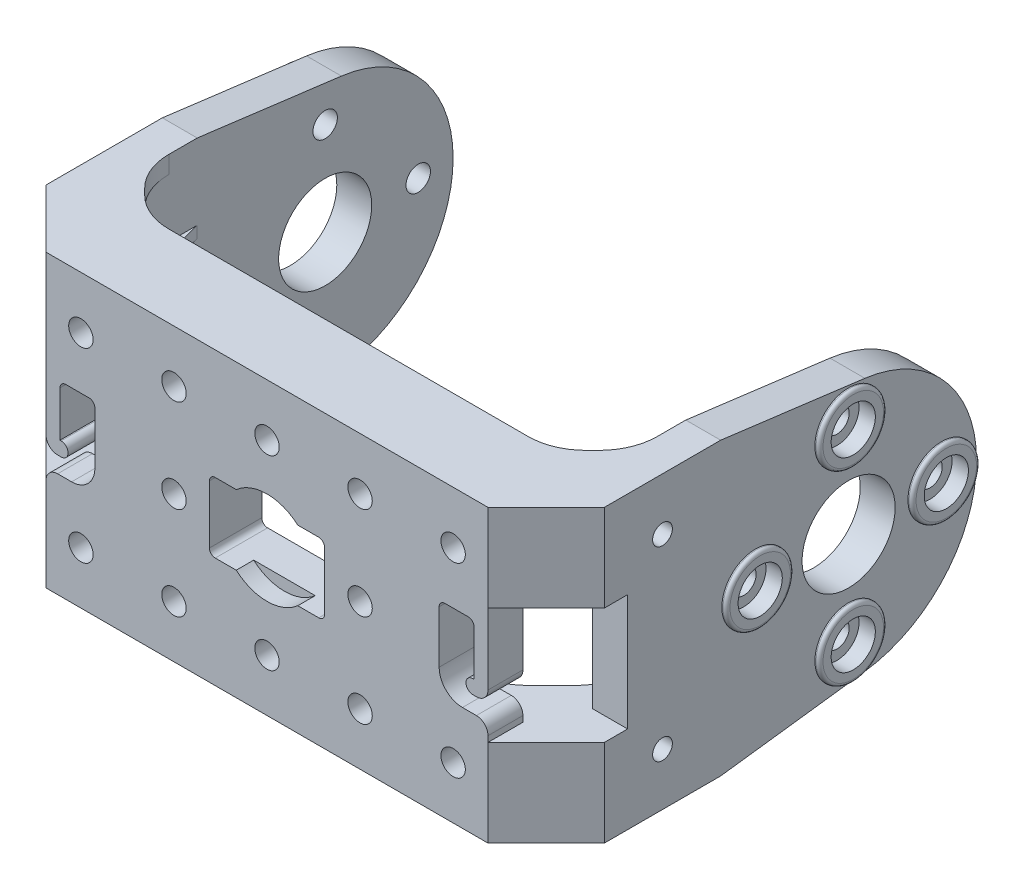
SolidWorks part; units mm, degrees
ref_plane "Front Plane" through (0, 0, 0) normal (0, 0, 1) x (1, 0, 0)
ref_plane "Top Plane" through (0, 0, 0) normal (0, 1, 0) x (1, 0, 0)
ref_plane "Right Plane" through (0, 0, 0) normal (1, 0, 0) x (0, 0, -1)
ref_plane "Plane1" through (0, 0, 23) normal (0, 0, 1) x (1, 0, 0)
sketch "Sketch1" plane through (0, 0, 23) normal (0, 0, 1) x (1, 0, 0)
  line L0 (-14.5956, -5) -> (10.0809, -5)
  line L1 (10.0809, -5) -> (10.0809, -2.4936)
  line L2 (10.0809, -2.4936) -> (11.2, -1.8475)
  line L3 (11.2, -1.8475) -> (11.2, 1.8475)
  line L4 (11.2, 1.8475) -> (10.0809, 2.4936)
  line L5 (10.0809, 2.4936) -> (10.0809, 3.5)
  line L6 (10.0809, 3.5) -> (14.5956, 5)
  line L7 (14.5956, 5) -> (-14.5956, 5)
  line L8 (-14.5956, 5) -> (-10.0809, 3.5)
  line L9 (-10.0809, 3.5) -> (-10.0809, 2.4936)
  line L10 (-10.0809, 2.4936) -> (-11.2, 1.8475)
  line L11 (-11.2, 1.8475) -> (-11.2, -1.8475)
  line L12 (-11.2, -1.8475) -> (-10.0809, -2.4936)
  line L13 (-10.0809, -2.4936) -> (-10.0809, -3.5)
  line L14 (-10.0809, -3.5) -> (-14.5956, -5)
extrude "Boss-Extrude1" add sketch "Sketch1" against normal blind 1
sketch "Sketch2" plane through (0, 0, 22) normal (0, 0, -1) x (-1, 0, 0)
  line L0 (-10.0809, -5) -> (-10.0809, 3.5)
  line L1 (-10.0809, 3.5) -> (-14.5956, 5)
  line L2 (-14.5956, 5) -> (14.5956, 5)
  line L3 (14.5956, 5) -> (10.0809, 3.5)
  line L4 (10.0809, 3.5) -> (10.0809, -3.5)
  line L5 (10.0809, -3.5) -> (14.5956, -5)
  line L6 (14.5956, -5) -> (-10.0809, -5)
extrude "Boss-Extrude2" add sketch "Sketch2" along normal blind 0.5
sketch "Sketch3" plane through (0, 0, 23) normal (0, 0, 1) x (1, 0, 0)
  line L0 (-8.3378, -3.5) -> (-10.0809, -2.4936)
  line L1 (-10.0809, -2.4936) -> (-10.0809, -3.5)
  line L2 (-10.0809, -3.5) -> (-8.3378, -3.5)
extrude "Cut-Extrude1" cut sketch "Sketch3" against normal blind 1
sketch "Sketch4" plane through (0, 0, 23) normal (0, 0, 1) x (1, 0, 0)
  line L0 (-10.0809, 2.4936) -> (-8.3378, 3.5)
  line L1 (-8.3378, 3.5) -> (-10.0809, 3.5)
  line L2 (-10.0809, 3.5) -> (-10.0809, 2.4936)
extrude "Cut-Extrude2" cut sketch "Sketch4" against normal blind 1
sketch "Sketch5" plane through (0, 0, 23) normal (0, 0, 1) x (1, 0, 0)
  line L0 (10.0809, -2.4936) -> (8.3378, -3.5)
  line L1 (8.3378, -3.5) -> (10.0809, -3.5)
  line L2 (10.0809, -3.5) -> (10.0809, -2.4936)
extrude "Cut-Extrude3" cut sketch "Sketch5" against normal blind 1
sketch "Sketch6" plane through (10.0809, 0, 0) normal (1, 0, 0) x (0, 0, -1)
  line L0 (-23, -5) -> (-23, -3.5)
  line L1 (-23, -3.5) -> (-21.5, -3.5)
  line L2 (-21.5, -3.5) -> (-21.5, -5)
  line L3 (-21.5, -5) -> (-23, -5)
extrude "Boss-Extrude3" add sketch "Sketch6" along normal blind 10.9191
sketch "Sketch7" plane through (0, 0, 23) normal (0, 0, 1) x (1, 0, 0)
  line L0 (8.3378, 3.5) -> (10.0809, 2.4936)
  line L1 (10.0809, 2.4936) -> (10.0809, 3.5)
  line L2 (10.0809, 3.5) -> (8.3378, 3.5)
extrude "Cut-Extrude4" cut sketch "Sketch7" against normal blind 1
sketch "Sketch8" plane through (0, -5, 0) normal (0, -1, 0) x (1, 0, 0)
  line L0 (-21, 11) -> (-21, 23)
  line L1 (-21, 23) -> (21, 23)
  line L2 (21, 23) -> (21, 11)
  line L3 (21, 11) -> (19.5, 17.0147)
  line L4 (19.5, 17.0147) -> (17.5147, 19)
  line L5 (17.5147, 19) -> (-17.5147, 19)
  line L6 (-17.5147, 19) -> (-19.5, 17.0147)
  line L7 (-19.5, 17.0147) -> (-21, 11)
extrude "Boss-Extrude4" add sketch "Sketch8" along normal blind 7.5
sketch "Sketch9" plane through (0, 5, 0) normal (0, 1, 0) x (-1, 0, 0)
  line L0 (21, 23) -> (21, 11)
  line L1 (21, 11) -> (19.5, 17.0147)
  line L2 (19.5, 17.0147) -> (17.5147, 19)
  line L3 (17.5147, 19) -> (-17.5147, 19)
  line L4 (-17.5147, 19) -> (-19.5, 17.0147)
  line L5 (-19.5, 17.0147) -> (-21, 11)
  line L6 (-21, 11) -> (-21, 23)
  line L7 (-21, 23) -> (21, 23)
extrude "Boss-Extrude5" add sketch "Sketch9" along normal blind 7.5
sketch "Sketch10" plane through (0, -5, 0) normal (0, 1, 0) x (-1, 0, 0)
  line L0 (-17.5147, 19) -> (17.5147, 19)
  line L1 (17.5147, 19) -> (15.0147, 21.5)
  line L2 (15.0147, 21.5) -> (-15.0147, 21.5)
  line L3 (-15.0147, 21.5) -> (-17.5147, 19)
extrude "Cut-Extrude5" cut sketch "Sketch10" against normal blind 6
sketch "Sketch11" plane through (0, 5, 0) normal (0, -1, 0) x (1, 0, 0)
  line L0 (-17.5147, 19) -> (17.5147, 19)
  line L1 (17.5147, 19) -> (15.0147, 21.5)
  line L2 (15.0147, 21.5) -> (-15.0147, 21.5)
  line L3 (-15.0147, 21.5) -> (-17.5147, 19)
extrude "Cut-Extrude6" cut sketch "Sketch11" against normal blind 6
sketch "Sketch12" plane through (-21, 0, 0) normal (-1, 0, 0) x (0, 0, 1)
  line L0 (23, 12.5) -> (23, 5)
  line L1 (23, 5) -> (19, 5)
  line L2 (19, 5) -> (19, -5)
  line L3 (19, -5) -> (23, -5)
  line L4 (23, -5) -> (23, -12.5)
  line L5 (23, -12.5) -> (11, -12.5)
  line L6 (11, -12.5) -> (-1.3986, -10.9107)
  line L7 (-1.3986, 10.9107) -> (11, 12.5)
  line L8 (11, 12.5) -> (23, 12.5)
  arc A0 (-1.3986, -10.9107) -> (-1.3986, 10.9107) centre (0, 0) cw
extrude "Boss-Extrude6" add sketch "Sketch12" along normal blind 3
sketch "Sketch13" plane through (21, 0, 0) normal (1, 0, 0) x (0, 0, -1)
  line L0 (-23, 12.5) -> (-11, 12.5)
  line L1 (-11, 12.5) -> (1.3986, 10.9107)
  line L2 (1.3986, -10.9107) -> (-11, -12.5)
  line L3 (-11, -12.5) -> (-23, -12.5)
  line L4 (-23, -12.5) -> (-23, -3.5)
  line L5 (-23, -3.5) -> (-21.5, -3.5)
  line L6 (-21.5, -3.5) -> (-21.5, -5)
  line L7 (-21.5, -5) -> (-19, -5)
  line L8 (-19, -5) -> (-19, 5)
  line L9 (-19, 5) -> (-23, 5)
  line L10 (-23, 5) -> (-23, 12.5)
  arc A0 (1.3986, 10.9107) -> (1.3986, -10.9107) centre (0, 0) cw
extrude "Boss-Extrude7" add sketch "Sketch13" along normal blind 3
sketch "Sketch14" plane through (0, 12.5, 0) normal (0, 1, 0) x (-1, 0, 0)
  line L0 (21, 11) -> (21, 15.5147)
  line L1 (21, 15.5147) -> (19.5, 17.0147)
  line L2 (19.5, 17.0147) -> (21, 11)
extrude "Cut-Extrude7" cut sketch "Sketch14" against normal blind 1.5
sketch "Sketch15" plane through (0, 12.5, 0) normal (0, 1, 0) x (-1, 0, 0)
  line L0 (-21, 11) -> (-19.5, 17.0147)
  line L1 (-19.5, 17.0147) -> (-21, 15.5147)
  line L2 (-21, 15.5147) -> (-21, 11)
extrude "Cut-Extrude8" cut sketch "Sketch15" against normal blind 1.5
sketch "Sketch16" plane through (0, 11, 0) normal (0, 1, 0) x (-1, 0, 0)
  line L0 (21, 22) -> (-21, 22)
  line L1 (-21, 22) -> (-21, 11)
  line L2 (-21, 11) -> (-19.5, 17.0147)
  line L3 (-19.5, 17.0147) -> (-15.0147, 21.5)
  line L4 (-15.0147, 21.5) -> (15.0147, 21.5)
  line L5 (15.0147, 21.5) -> (19.5, 17.0147)
  line L6 (19.5, 17.0147) -> (21, 11)
  line L7 (21, 11) -> (21, 22)
extrude "Cut-Extrude9" cut sketch "Sketch16" against normal blind 5
sketch "Sketch17" plane through (10.0809, 0, 0) normal (1, 0, 0) x (0, 0, -1)
  line L0 (-21.5, 3.5) -> (-22, 3.5)
  line L1 (-22, 3.5) -> (-22, -3.5)
  line L2 (-22, -3.5) -> (-21.5, -3.5)
  line L3 (-21.5, -3.5) -> (-21.5, 3.5)
extrude "Cut-Extrude10" cut sketch "Sketch17" against normal blind 1.7431
sketch "Sketch18" plane through (0, -12.5, 0) normal (0, -1, 0) x (1, 0, 0)
  line L0 (-19.5, 17.0147) -> (-21, 15.5147)
  line L1 (-21, 15.5147) -> (-21, 11)
  line L2 (-21, 11) -> (-19.5, 17.0147)
extrude "Cut-Extrude11" cut sketch "Sketch18" against normal blind 1.5
sketch "Sketch19" plane through (0, -12.5, 0) normal (0, -1, 0) x (1, 0, 0)
  line L0 (21, 15.5147) -> (19.5, 17.0147)
  line L1 (19.5, 17.0147) -> (21, 11)
  line L2 (21, 11) -> (21, 15.5147)
extrude "Cut-Extrude12" cut sketch "Sketch19" against normal blind 1.5
sketch "Sketch20" plane through (0, -11, 0) normal (0, -1, 0) x (1, 0, 0)
  line L0 (21, 22) -> (-21, 22)
  line L1 (-21, 22) -> (-21, 11)
  line L2 (-21, 11) -> (-19.5, 17.0147)
  line L3 (-19.5, 17.0147) -> (-15.0147, 21.5)
  line L4 (-15.0147, 21.5) -> (15.0147, 21.5)
  line L5 (15.0147, 21.5) -> (19.5, 17.0147)
  line L6 (19.5, 17.0147) -> (21, 11)
  line L7 (21, 11) -> (21, 22)
extrude "Cut-Extrude13" cut sketch "Sketch20" against normal blind 5
sketch "Sketch21" plane through (8.3378, 0, 0) normal (1, 0, 0) x (0, 0, -1)
  line L0 (-21.5, 3.5) -> (-22, 3.5)
  line L1 (-22, 3.5) -> (-22, -3.5)
  line L2 (-22, -3.5) -> (-21.5, -3.5)
  line L3 (-21.5, -3.5) -> (-21.5, 3.5)
extrude "Cut-Extrude14" cut sketch "Sketch21" against normal blind 2.3378
sketch "Sketch22" plane through (-10.0809, 0, 0) normal (-1, 0, 0) x (0, 0, 1)
  line L0 (21.5, -3.5) -> (22, -3.5)
  line L1 (22, -3.5) -> (22, 3.5)
  line L2 (22, 3.5) -> (21.5, 3.5)
  line L3 (21.5, 3.5) -> (21.5, -3.5)
extrude "Cut-Extrude15" cut sketch "Sketch22" against normal blind 1.7431
sketch "Sketch23" plane through (24, 0, 0) normal (1, 0, 0) x (0, 0, -1)
  line L0 (-21.5, -3.5) -> (-23, -3.5)
  line L1 (-23, -3.5) -> (-23, -5)
  line L2 (-23, -5) -> (-21.5, -5)
  line L3 (-21.5, -5) -> (-21.5, -3.5)
extrude "Cut-Extrude16" cut sketch "Sketch23" against normal blind 8.9853
sketch "Sketch24" plane through (-8.3378, 0, 0) normal (-1, 0, 0) x (0, 0, 1)
  line L0 (21.5, -3.5) -> (22, -3.5)
  line L1 (22, -3.5) -> (22, 3.5)
  line L2 (22, 3.5) -> (21.5, 3.5)
  line L3 (21.5, 3.5) -> (21.5, -3.5)
extrude "Cut-Extrude17" cut sketch "Sketch24" against normal blind 2.3378
sketch "Sketch25" plane through (15.0147, 0, 0) normal (1, 0, 0) x (0, 0, -1)
  line L0 (-21.5, -3.5) -> (-23, -3.5)
  line L1 (-23, -3.5) -> (-23, -5)
  line L2 (-23, -5) -> (-21.5, -5)
  line L3 (-21.5, -5) -> (-21.5, -3.5)
extrude "Cut-Extrude18" cut sketch "Sketch25" against normal blind 0.4191
sketch "Sketch26" plane through (0, 0, 23) normal (0, 0, 1) x (1, 0, 0)
  line L0 (14.8, 3.5) -> (14.8, -3.5)
  line L1 (14.8, -3.5) -> (19, -3.5)
  line L2 (19, -3.5) -> (19, -5)
  line L3 (19, -5) -> (24, -5)
  line L4 (24, -5) -> (24, -12.5)
  line L5 (24, -12.5) -> (-24, -12.5)
  line L6 (-24, -12.5) -> (-24, -5)
  line L7 (-24, -5) -> (-19, -5)
  line L8 (-19, -5) -> (-19, -3.5)
  line L9 (-19, -3.5) -> (-14.8, -3.5)
  line L10 (-14.8, -3.5) -> (-14.8, 3.5)
  line L11 (-14.8, 3.5) -> (-17.8, 3.5)
  line L12 (-17.8, 3.5) -> (-17.8, -0.9)
  line L13 (-17.8, -0.9) -> (-17.7, -0.9)
  line L14 (-17.7, -2.1) -> (-19, -2.1)
  line L15 (-19, -2.1) -> (-19, 5)
  line L16 (-19, 5) -> (-24, 5)
  line L17 (-24, 5) -> (-24, 12.5)
  line L18 (-24, 12.5) -> (24, 12.5)
  line L19 (24, 12.5) -> (24, 5)
  line L20 (24, 5) -> (19, 5)
  line L21 (19, 5) -> (19, -2.1)
  line L22 (19, -2.1) -> (17.7, -2.1)
  line L23 (17.7, -0.9) -> (17.8, -0.9)
  line L24 (17.8, -0.9) -> (17.8, 3.5)
  line L25 (17.8, 3.5) -> (14.8, 3.5)
  arc A0 (-17.7, -0.9) -> (-17.7, -2.1) centre (-17.7, -1.5) cw
  arc A1 (17.7, -2.1) -> (17.7, -0.9) centre (17.7, -1.5) cw
extrude "Boss-Extrude8" add sketch "Sketch26" along normal blind 3
sketch "Sketch27" plane through (0, 0, 21.5) normal (0, 0, -1) x (-1, 0, 0)
  line L0 (-9.9191, 4.5) -> (9.9191, 4.5)
  line L1 (9.9191, 4.5) -> (14.4338, 6)
  line L2 (14.4338, 6) -> (-14.4338, 6)
  line L3 (-14.4338, 6) -> (-9.9191, 4.5)
extrude "Cut-Extrude19" cut sketch "Sketch27" against normal blind 0.5
sketch "Sketch28" plane through (0, 0, 22) normal (0, 0, -1) x (-1, 0, 0)
  line L0 (9.9191, 4.5) -> (13.8102, 5.7928)
  line L1 (13.8102, 5.7928) -> (12.5359, 8)
  line L2 (12.5359, 8) -> (14.2679, 11)
  line L3 (14.2679, 11) -> (9.2038, 11)
  line L4 (9.2038, 11) -> (11.2, 9.8475)
  line L5 (11.2, 9.8475) -> (11.2, 6.1525)
  line L6 (11.2, 6.1525) -> (8.3378, 4.5)
  line L7 (8.3378, 4.5) -> (9.9191, 4.5)
extrude "Cut-Extrude20" cut sketch "Sketch28" against normal blind 1
sketch "Sketch29" plane through (0, 0, 22) normal (0, 0, -1) x (-1, 0, 0)
  line L0 (7.6622, 4.5) -> (4.8, 6.1525)
  line L1 (4.8, 6.1525) -> (4.8, 9.8475)
  line L2 (4.8, 9.8475) -> (6.7962, 11)
  line L3 (6.7962, 11) -> (1.2038, 11)
  line L4 (1.2038, 11) -> (3.2, 9.8475)
  line L5 (3.2, 9.8475) -> (3.2, 6.1525)
  line L6 (3.2, 6.1525) -> (0.3378, 4.5)
  line L7 (0.3378, 4.5) -> (7.6622, 4.5)
extrude "Cut-Extrude21" cut sketch "Sketch29" against normal blind 1
sketch "Sketch30" plane through (0, 0, 22) normal (0, 0, -1) x (-1, 0, 0)
  line L0 (-8.3378, 4.5) -> (-11.2, 6.1525)
  line L1 (-11.2, 6.1525) -> (-11.2, 9.8475)
  line L2 (-11.2, 9.8475) -> (-9.2038, 11)
  line L3 (-9.2038, 11) -> (-14.2679, 11)
  line L4 (-14.2679, 11) -> (-12.5359, 8)
  line L5 (-12.5359, 8) -> (-13.8102, 5.7928)
  line L6 (-13.8102, 5.7928) -> (-9.9191, 4.5)
  line L7 (-9.9191, 4.5) -> (-8.3378, 4.5)
extrude "Cut-Extrude22" cut sketch "Sketch30" against normal blind 1
sketch "Sketch31" plane through (0, 0, 21.5) normal (0, 0, -1) x (-1, 0, 0)
  line L0 (9.9191, -4.5) -> (-9.9191, -4.5)
  line L1 (-9.9191, -4.5) -> (-14.4338, -6)
  line L2 (-14.4338, -6) -> (14.4338, -6)
  line L3 (14.4338, -6) -> (9.9191, -4.5)
extrude "Cut-Extrude23" cut sketch "Sketch31" against normal blind 0.5
sketch "Sketch32" plane through (0, 0, 22) normal (0, 0, -1) x (-1, 0, 0)
  line L0 (-7.6622, -4.5) -> (-4.8, -6.1525)
  line L1 (-4.8, -6.1525) -> (-4.8, -9.8475)
  line L2 (-4.8, -9.8475) -> (-6.7962, -11)
  line L3 (-6.7962, -11) -> (-1.2038, -11)
  line L4 (-1.2038, -11) -> (-3.2, -9.8475)
  line L5 (-3.2, -9.8475) -> (-3.2, -6.1525)
  line L6 (-3.2, -6.1525) -> (-0.3378, -4.5)
  line L7 (-0.3378, -4.5) -> (-7.6622, -4.5)
extrude "Cut-Extrude24" cut sketch "Sketch32" against normal blind 1
sketch "Sketch33" plane through (0, 0, 22) normal (0, 0, -1) x (-1, 0, 0)
  line L0 (-9.9191, -4.5) -> (-13.8102, -5.7928)
  line L1 (-13.8102, -5.7928) -> (-12.5359, -8)
  line L2 (-12.5359, -8) -> (-14.2679, -11)
  line L3 (-14.2679, -11) -> (-9.2038, -11)
  line L4 (-9.2038, -11) -> (-11.2, -9.8475)
  line L5 (-11.2, -9.8475) -> (-11.2, -6.1525)
  line L6 (-11.2, -6.1525) -> (-8.3378, -4.5)
  line L7 (-8.3378, -4.5) -> (-9.9191, -4.5)
extrude "Cut-Extrude25" cut sketch "Sketch33" against normal blind 1
sketch "Sketch34" plane through (0, 0, 22) normal (0, 0, -1) x (-1, 0, 0)
  line L0 (-0.3378, 4.5) -> (-3.2, 6.1525)
  line L1 (-3.2, 6.1525) -> (-3.2, 9.8475)
  line L2 (-3.2, 9.8475) -> (-1.2038, 11)
  line L3 (-1.2038, 11) -> (-6.7962, 11)
  line L4 (-6.7962, 11) -> (-4.8, 9.8475)
  line L5 (-4.8, 9.8475) -> (-4.8, 6.1525)
  line L6 (-4.8, 6.1525) -> (-7.6622, 4.5)
  line L7 (-7.6622, 4.5) -> (-0.3378, 4.5)
extrude "Cut-Extrude26" cut sketch "Sketch34" against normal blind 1
sketch "Sketch35" plane through (0, 0, 22) normal (0, 0, -1) x (-1, 0, 0)
  line L0 (8.3378, -4.5) -> (11.2, -6.1525)
  line L1 (11.2, -6.1525) -> (11.2, -9.8475)
  line L2 (11.2, -9.8475) -> (9.2038, -11)
  line L3 (9.2038, -11) -> (14.2679, -11)
  line L4 (14.2679, -11) -> (12.5359, -8)
  line L5 (12.5359, -8) -> (13.8102, -5.7928)
  line L6 (13.8102, -5.7928) -> (9.9191, -4.5)
  line L7 (9.9191, -4.5) -> (8.3378, -4.5)
extrude "Cut-Extrude27" cut sketch "Sketch35" against normal blind 1
sketch "Sketch36" plane through (0, 0, 22) normal (0, 0, -1) x (-1, 0, 0)
  line L0 (0.3378, -4.5) -> (3.2, -6.1525)
  line L1 (3.2, -6.1525) -> (3.2, -9.8475)
  line L2 (3.2, -9.8475) -> (1.2038, -11)
  line L3 (1.2038, -11) -> (6.7962, -11)
  line L4 (6.7962, -11) -> (4.8, -9.8475)
  line L5 (4.8, -9.8475) -> (4.8, -6.1525)
  line L6 (4.8, -6.1525) -> (7.6622, -4.5)
  line L7 (7.6622, -4.5) -> (0.3378, -4.5)
extrude "Cut-Extrude28" cut sketch "Sketch36" against normal blind 1
sketch "Sketch37" plane through (0, 0, 22) normal (0, 0, -1) x (-1, 0, 0)
  line L0 (-13.6906, -8) -> (-14.8453, -6)
  line L1 (-14.8453, -6) -> (-17.1547, -6)
  line L2 (-17.1547, -6) -> (-18.3094, -8)
  line L3 (-18.3094, -8) -> (-17.1547, -10)
  line L4 (-17.1547, -10) -> (-14.8453, -10)
  line L5 (-14.8453, -10) -> (-13.6906, -8)
extrude "Cut-Extrude29" cut sketch "Sketch37" against normal blind 2
sketch "Sketch38" plane through (0, 0, 22) normal (0, 0, -1) x (-1, 0, 0)
  line L0 (-17.7321, -11) -> (-19.4641, -8)
  line L1 (-19.4641, -8) -> (-18.3094, -6)
  line L2 (-18.3094, -6) -> (-21, -6)
  line L3 (-21, -6) -> (-21, -11)
  line L4 (-21, -11) -> (-17.7321, -11)
extrude "Cut-Extrude30" cut sketch "Sketch38" against normal blind 1
sketch "Sketch39" plane through (0, 0, 22) normal (0, 0, -1) x (-1, 0, 0)
  line L0 (-14.8453, 10) -> (-17.1547, 10)
  line L1 (-17.1547, 10) -> (-18.3094, 8)
  line L2 (-18.3094, 8) -> (-17.1547, 6)
  line L3 (-17.1547, 6) -> (-14.8453, 6)
  line L4 (-14.8453, 6) -> (-13.6906, 8)
  line L5 (-13.6906, 8) -> (-14.8453, 10)
extrude "Cut-Extrude31" cut sketch "Sketch39" against normal blind 2
sketch "Sketch40" plane through (0, 0, 22) normal (0, 0, -1) x (-1, 0, 0)
  line L0 (-17.7321, 11) -> (-21, 11)
  line L1 (-21, 11) -> (-21, 6)
  line L2 (-21, 6) -> (-18.3094, 6)
  line L3 (-18.3094, 6) -> (-19.4641, 8)
  line L4 (-19.4641, 8) -> (-17.7321, 11)
extrude "Cut-Extrude32" cut sketch "Sketch40" against normal blind 1
sketch "Sketch41" plane through (0, 0, 22) normal (0, 0, -1) x (-1, 0, 0)
  line L0 (13.6906, 8) -> (14.8453, 6)
  line L1 (14.8453, 6) -> (17.1547, 6)
  line L2 (17.1547, 6) -> (18.3094, 8)
  line L3 (18.3094, 8) -> (17.1547, 10)
  line L4 (17.1547, 10) -> (14.8453, 10)
  line L5 (14.8453, 10) -> (13.6906, 8)
extrude "Cut-Extrude33" cut sketch "Sketch41" against normal blind 2
sketch "Sketch42" plane through (0, 0, 22) normal (0, 0, -1) x (-1, 0, 0)
  line L0 (17.7321, 11) -> (19.4641, 8)
  line L1 (19.4641, 8) -> (18.3094, 6)
  line L2 (18.3094, 6) -> (21, 6)
  line L3 (21, 6) -> (21, 11)
  line L4 (21, 11) -> (17.7321, 11)
extrude "Cut-Extrude34" cut sketch "Sketch42" against normal blind 1
sketch "Sketch43" plane through (0, 0, 22) normal (0, 0, -1) x (-1, 0, 0)
  line L0 (14.8453, -10) -> (17.1547, -10)
  line L1 (17.1547, -10) -> (18.3094, -8)
  line L2 (18.3094, -8) -> (17.1547, -6)
  line L3 (17.1547, -6) -> (14.8453, -6)
  line L4 (14.8453, -6) -> (13.6906, -8)
  line L5 (13.6906, -8) -> (14.8453, -10)
extrude "Cut-Extrude35" cut sketch "Sketch43" against normal blind 2
sketch "Sketch44" plane through (0, 0, 22) normal (0, 0, -1) x (-1, 0, 0)
  line L0 (17.7321, -11) -> (21, -11)
  line L1 (21, -11) -> (21, -6)
  line L2 (21, -6) -> (18.3094, -6)
  line L3 (18.3094, -6) -> (19.4641, -8)
  line L4 (19.4641, -8) -> (17.7321, -11)
extrude "Cut-Extrude36" cut sketch "Sketch44" against normal blind 1
sketch "Sketch45" plane through (0, 0, 22) normal (0, 0, -1) x (-1, 0, 0)
  line L0 (-8, 2.3094) -> (-10, 1.1547)
  line L1 (-10, 1.1547) -> (-10, -1.1547)
  line L2 (-10, -1.1547) -> (-8, -2.3094)
  line L3 (-8, -2.3094) -> (-6, -1.1547)
  line L4 (-6, -1.1547) -> (-6, 1.1547)
  line L5 (-6, 1.1547) -> (-8, 2.3094)
extrude "Cut-Extrude37" cut sketch "Sketch45" against normal blind 2
sketch "Sketch46" plane through (0, 0, 22) normal (0, 0, -1) x (-1, 0, 0)
  line L0 (-6, 3.5) -> (-7.6622, 3.5)
  line L1 (-7.6622, 3.5) -> (-6, 2.5403)
  line L2 (-6, 2.5403) -> (-6, 3.5)
extrude "Cut-Extrude38" cut sketch "Sketch46" against normal blind 1
sketch "Sketch47" plane through (0, 0, 22) normal (0, 0, -1) x (-1, 0, 0)
  line L0 (-6, -2.5403) -> (-7.6622, -3.5)
  line L1 (-7.6622, -3.5) -> (-6, -3.5)
  line L2 (-6, -3.5) -> (-6, -2.5403)
extrude "Cut-Extrude39" cut sketch "Sketch47" against normal blind 1
sketch "Sketch48" plane through (0, 0, 22) normal (0, 0, -1) x (-1, 0, 0)
  line L0 (8, 2.3094) -> (6, 1.1547)
  line L1 (6, 1.1547) -> (6, -1.1547)
  line L2 (6, -1.1547) -> (8, -2.3094)
  line L3 (8, -2.3094) -> (10, -1.1547)
  line L4 (10, -1.1547) -> (10, 1.1547)
  line L5 (10, 1.1547) -> (8, 2.3094)
extrude "Cut-Extrude40" cut sketch "Sketch48" against normal blind 2
sketch "Sketch49" plane through (0, 0, 22) normal (0, 0, -1) x (-1, 0, 0)
  line L0 (6, -3.5) -> (7.6622, -3.5)
  line L1 (7.6622, -3.5) -> (6, -2.5403)
  line L2 (6, -2.5403) -> (6, -3.5)
extrude "Cut-Extrude41" cut sketch "Sketch49" against normal blind 1
sketch "Sketch50" plane through (0, 0, 22) normal (0, 0, -1) x (-1, 0, 0)
  line L0 (6, 2.5403) -> (7.6622, 3.5)
  line L1 (7.6622, 3.5) -> (6, 3.5)
  line L2 (6, 3.5) -> (6, 2.5403)
extrude "Cut-Extrude42" cut sketch "Sketch50" against normal blind 1
sketch "Sketch51" plane through (0, 0, 26) normal (0, 0, 1) x (1, 0, 0)
  line L0 (-4.95, 3) -> (-4.95, -3)
  line L1 (-4.95, -3) -> (4.95, -3)
  line L2 (4.95, -3) -> (4.95, 3)
  line L3 (4.95, 3) -> (-4.95, 3)
extrude "Cut-Extrude43" cut sketch "Sketch51" against normal through all
sketch "Sketch52" plane through (0, 0, 26) normal (0, 0, 1) x (1, 0, 0)
  line L0 (2.6458, -3) -> (-2.6458, -3)
  arc A0 (-2.6458, -3) -> (2.6458, -3) centre (0, 0) ccw
extrude "Cut-Extrude44" cut sketch "Sketch52" against normal blind 1.5
sketch "Sketch53" plane through (0, 0, 26) normal (0, 0, 1) x (1, 0, 0)
  line L0 (-2.6458, 3) -> (2.6458, 3)
  arc A0 (2.6458, 3) -> (-2.6458, 3) centre (0, 0) ccw
extrude "Cut-Extrude45" cut sketch "Sketch53" against normal blind 1.5
sketch "Sketch54" plane through (0, 0, 22) normal (0, 0, -1) x (-1, 0, 0)
  line L0 (2, -6.8453) -> (0, -5.6906)
  line L1 (0, -5.6906) -> (-2, -6.8453)
  line L2 (-2, -6.8453) -> (-2, -9.1547)
  line L3 (-2, -9.1547) -> (0, -10.3094)
  line L4 (0, -10.3094) -> (2, -9.1547)
  line L5 (2, -9.1547) -> (2, -6.8453)
extrude "Cut-Extrude46" cut sketch "Sketch54" against normal blind 2
sketch "Sketch55" plane through (0, 0, 22) normal (0, 0, -1) x (-1, 0, 0)
  line L0 (-6, 9.1547) -> (-8, 10.3094)
  line L1 (-8, 10.3094) -> (-10, 9.1547)
  line L2 (-10, 9.1547) -> (-10, 6.8453)
  line L3 (-10, 6.8453) -> (-8, 5.6906)
  line L4 (-8, 5.6906) -> (-6, 6.8453)
  line L5 (-6, 6.8453) -> (-6, 9.1547)
extrude "Cut-Extrude47" cut sketch "Sketch55" against normal blind 2
sketch "Sketch56" plane through (0, 0, 22) normal (0, 0, -1) x (-1, 0, 0)
  line L0 (2, 9.1547) -> (0, 10.3094)
  line L1 (0, 10.3094) -> (-2, 9.1547)
  line L2 (-2, 9.1547) -> (-2, 6.8453)
  line L3 (-2, 6.8453) -> (0, 5.6906)
  line L4 (0, 5.6906) -> (2, 6.8453)
  line L5 (2, 6.8453) -> (2, 9.1547)
extrude "Cut-Extrude48" cut sketch "Sketch56" against normal blind 2
sketch "Sketch57" plane through (0, 0, 22) normal (0, 0, -1) x (-1, 0, 0)
  line L0 (10, 9.1547) -> (8, 10.3094)
  line L1 (8, 10.3094) -> (6, 9.1547)
  line L2 (6, 9.1547) -> (6, 6.8453)
  line L3 (6, 6.8453) -> (8, 5.6906)
  line L4 (8, 5.6906) -> (10, 6.8453)
  line L5 (10, 6.8453) -> (10, 9.1547)
extrude "Cut-Extrude49" cut sketch "Sketch57" against normal blind 2
sketch "Sketch58" plane through (0, 0, 22) normal (0, 0, -1) x (-1, 0, 0)
  line L0 (10, -6.8453) -> (8, -5.6906)
  line L1 (8, -5.6906) -> (6, -6.8453)
  line L2 (6, -6.8453) -> (6, -9.1547)
  line L3 (6, -9.1547) -> (8, -10.3094)
  line L4 (8, -10.3094) -> (10, -9.1547)
  line L5 (10, -9.1547) -> (10, -6.8453)
extrude "Cut-Extrude50" cut sketch "Sketch58" against normal blind 2
sketch "Sketch59" plane through (0, 0, 22) normal (0, 0, -1) x (-1, 0, 0)
  line L0 (-6, -6.8453) -> (-8, -5.6906)
  line L1 (-8, -5.6906) -> (-10, -6.8453)
  line L2 (-10, -6.8453) -> (-10, -9.1547)
  line L3 (-10, -9.1547) -> (-8, -10.3094)
  line L4 (-8, -10.3094) -> (-6, -9.1547)
  line L5 (-6, -9.1547) -> (-6, -6.8453)
extrude "Cut-Extrude51" cut sketch "Sketch59" against normal blind 2
draft "Draft1" type of draft neutral plane draft angle 71.621 faces to draft 1 face at (14.5956, -4.25, 22.25) neutral plane through (0, -5, 0) neutral plane normal (0, 1, 0) parameters "D1"=71.621
sketch "Sketch60" plane through (0, 0, 0) normal (0, 0, 1) x (1, 0, 0)
  line L0 (24, 10.9) -> (24, 8)
  line L1 (24, 8) -> (24.4, 8)
  line L2 (24.4, 8) -> (24.4, 10.9)
  line L3 (24.4, 10.9) -> (24, 10.9)
  line L4 (24, 8) -> (24.4, 8) construction
revolve "Revolve1" add sketch "Sketch60" angle 360 about L4
ref_plane "Plane2" through (0, 0, -8) normal (0, 0, 1) x (1, 0, 0)
sketch "Sketch61" plane through (0, 0, -8) normal (0, 0, 1) x (1, 0, 0)
  line L0 (24, 2.9) -> (24, 0)
  line L1 (24, 0) -> (24.4, 0)
  line L2 (24.4, 0) -> (24.4, 2.9)
  line L3 (24.4, 2.9) -> (24, 2.9)
  line L4 (24, 0) -> (24.4, 0) construction
revolve "Revolve2" add sketch "Sketch61" angle 360 about L4
sketch "Sketch62" plane through (0, 0, 0) normal (0, 0, 1) x (1, 0, 0)
  line L0 (24, -5.1) -> (24, -8)
  line L1 (24, -8) -> (24.4, -8)
  line L2 (24.4, -8) -> (24.4, -5.1)
  line L3 (24.4, -5.1) -> (24, -5.1)
  line L4 (24, -8) -> (24.4, -8) construction
revolve "Revolve3" add sketch "Sketch62" angle 360 about L4
ref_plane "Plane3" through (0, 0, 8) normal (0, 0, 1) x (1, 0, 0)
sketch "Sketch63" plane through (0, 0, 8) normal (0, 0, 1) x (1, 0, 0)
  line L0 (24, 2.9) -> (24, 0)
  line L1 (24, 0) -> (24.4, 0)
  line L2 (24.4, 0) -> (24.4, 2.9)
  line L3 (24.4, 2.9) -> (24, 2.9)
  line L4 (24, 0) -> (24.4, 0) construction
revolve "Revolve4" add sketch "Sketch63" angle 360 about L4
ref_plane "Plane4" through (0, 0, -8) normal (0, 0, -1) x (-1, 0, 0)
sketch "Sketch64" plane through (0, 0, -8) normal (0, 0, -1) x (-1, 0, 0)
  line L0 (24, 2.9) -> (24, 0)
  line L1 (24, 0) -> (24.4, 0)
  line L2 (24.4, 0) -> (24.4, 2.9)
  line L3 (24.4, 2.9) -> (24, 2.9)
  line L4 (24, 0) -> (24.4, 0) construction
revolve "Revolve5" add sketch "Sketch64" angle 360 about L4
ref_plane "Plane5" through (0, 0, 0) normal (0, 0, -1) x (-1, 0, 0)
sketch "Sketch65" plane through (0, 0, 0) normal (0, 0, -1) x (-1, 0, 0)
  line L0 (24, 10.9) -> (24, 8)
  line L1 (24, 8) -> (24.4, 8)
  line L2 (24.4, 8) -> (24.4, 10.9)
  line L3 (24.4, 10.9) -> (24, 10.9)
  line L4 (24, 8) -> (24.4, 8) construction
revolve "Revolve6" add sketch "Sketch65" angle 360 about L4
ref_plane "Plane6" through (0, 0, 8) normal (0, 0, -1) x (-1, 0, 0)
sketch "Sketch66" plane through (0, 0, 8) normal (0, 0, -1) x (-1, 0, 0)
  line L0 (24, 2.9) -> (24, 0)
  line L1 (24, 0) -> (24.4, 0)
  line L2 (24.4, 0) -> (24.4, 2.9)
  line L3 (24.4, 2.9) -> (24, 2.9)
  line L4 (24, 0) -> (24.4, 0) construction
revolve "Revolve7" add sketch "Sketch66" angle 360 about L4
sketch "Sketch67" plane through (0, 0, 0) normal (0, 0, -1) x (-1, 0, 0)
  line L0 (24, -5.1) -> (24, -8)
  line L1 (24, -8) -> (24.4, -8)
  line L2 (24.4, -8) -> (24.4, -5.1)
  line L3 (24.4, -5.1) -> (24, -5.1)
  line L4 (24, -8) -> (24.4, -8) construction
revolve "Revolve8" add sketch "Sketch67" angle 360 about L4
hole_wizard "Ø1.7 (1.7) Diameter Hole1" positions "Sketch69" profile "Sketch68" hole size "Ø1.7" standard "ANSI Metric"
sketch "Sketch69" plane through (24, 0, 0) normal (1, 0, 0) x (0, 0, -1)
  point P0 (-16, -8)
  point P1 (-16, 8)
sketch "Sketch68" plane through (24, -8, 16) normal (0, 1, 0) x (0, 0, -1)
  line L0 (0, 0) -> (0, 3)
  line L1 (0, 3) -> (0.85, 3)
  line L2 (0.85, 3) -> (0.85, 0)
  line L5 (0.85, 0) -> (0, 0)
  line L11 (0, -6.35) -> (0, 107.95) construction
  dimension "Thru Hole Dia." = 1.7
  dimension "Thru Hole Depth" = 3
hole_wizard "Ø1.7 (1.7) Diameter Hole2" positions "Sketch71" profile "Sketch70" hole size "Ø1.7" standard "ANSI Metric"
sketch "Sketch71" plane through (-21, 0, 0) normal (1, 0, 0) x (0, 0, -1)
  point P0 (-16, -8)
  point P1 (-16, 8)
sketch "Sketch70" plane through (-21, -8, 16) normal (0, 1, 0) x (0, 0, -1)
  line L0 (0, 0) -> (0, 3.4)
  line L1 (0, 3.4) -> (0.85, 3.4)
  line L2 (0.85, 3.4) -> (0.85, 0)
  line L5 (0.85, 0) -> (0, 0)
  line L11 (0, -6.35) -> (0, 107.95) construction
  dimension "Thru Hole Dia." = 1.7
  dimension "Thru Hole Depth" = 3.4
hole_wizard "Ø2.1 (2.1) Diameter Hole1" positions "Sketch73" profile "Sketch72" hole size "Ø2.1" standard "ANSI Metric"
sketch "Sketch73" plane through (0, 0, 26) normal (0, 0, 1) x (1, 0, 0)
  point P0 (0, -8)
  point P1 (8, 8)
  point P2 (0, 8)
  point P3 (-8, 8)
  point P4 (-8, -8)
  point P5 (8, -8)
  point P6 (-16, 8)
  point P7 (8, 0)
  point P8 (16, 8)
  point P9 (16, -8)
  point P10 (-8, 0)
  point P11 (-16, -8)
sketch "Sketch72" plane through (0, -8, 26) normal (1, 0, 0) x (0, -1, 0)
  line L0 (0, 0) -> (0, 37)
  line L1 (0, 37) -> (1.05, 37)
  line L2 (1.05, 37) -> (1.05, 0)
  line L5 (1.05, 0) -> (0, 0)
  line L11 (0, -6.35) -> (0, 107.95) construction
  dimension "Thru Hole Dia." = 2.1
  dimension "Thru Hole Depth" = 37
hole_wizard "Hole1" positions "Sketch75" profile "Sketch74" legacy
sketch "Sketch75" plane through (24.4, 0, 0) normal (1, 0, 0) x (0, 0, -1)
  point P0 (-8, 0)
  point P1 (0, -8)
  point P2 (8, 0)
  point P3 (0, 8)
sketch "Sketch74" plane through (24.4, 0, 8) normal (0, 1, 0) x (0, 0, -1)
  line L0 (0, 0) -> (0, 3.4)
  line L1 (0, 3.4) -> (1.05, 3.4)
  line L2 (1.05, 3.4) -> (1.05, 1.4)
  line L3 (1.05, 1.4) -> (1.9, 1.4)
  line L4 (1.9, 1.4) -> (1.9, 0)
  line L5 (1.9, 0) -> (0, 0)
  line L6 (0, 110) -> (0, -10) construction
  dimension "Diameter" = 2.1
  dimension "Depth" = 3.4
  dimension "C-Bore Diameter" = 3.8
  dimension "C-Bore Depth" = 1.4
hole_wizard "Hole2" positions "Sketch77" profile "Sketch76" legacy
sketch "Sketch77" plane through (-24.4, 0, 0) normal (-1, 0, 0) x (0, 0, 1)
  point P0 (8, 0)
  point P1 (0, -8)
  point P2 (0, 8)
  point P3 (-8, 0)
sketch "Sketch76" plane through (-24.4, 0, 8) normal (0, 1, 0) x (0, 0, 1)
  line L0 (0, 0) -> (0, 48.8)
  line L1 (0, 48.8) -> (1.05, 48.8)
  line L2 (1.05, 48.8) -> (1.05, 1.4)
  line L3 (1.05, 1.4) -> (1.9, 1.4)
  line L4 (1.9, 1.4) -> (1.9, 0)
  line L5 (1.9, 0) -> (0, 0)
  line L6 (0, 110) -> (0, -10) construction
  dimension "Diameter" = 2.1
  dimension "Depth" = 48.8
  dimension "C-Bore Diameter" = 3.8
  dimension "C-Bore Depth" = 1.4
hole_wizard "Ø8.0 (8) Diameter Hole1" positions "Sketch79" profile "Sketch78" hole size "Ø8.0" standard "ANSI Metric"
sketch "Sketch79" plane through (24, 0, 0) normal (1, 0, 0) x (0, 0, -1)
  point P0 (0, 0)
sketch "Sketch78" plane through (24, 0, 0) normal (0, 1, 0) x (0, 0, -1)
  line L0 (0, 0) -> (0, 3)
  line L1 (0, 3) -> (4, 3)
  line L2 (4, 3) -> (4, 0)
  line L5 (4, 0) -> (0, 0)
  line L11 (0, -6.35) -> (0, 107.95) construction
  dimension "Thru Hole Dia." = 8
  dimension "Thru Hole Depth" = 3
hole_wizard "Ø8.0 (8) Diameter Hole2" positions "Sketch81" profile "Sketch80" hole size "Ø8.0" standard "ANSI Metric"
sketch "Sketch81" plane through (-21, 0, 0) normal (1, 0, 0) x (0, 0, -1)
  point P0 (0, 0)
sketch "Sketch80" plane through (-21, 0, 0) normal (0, 1, 0) x (0, 0, -1)
  line L0 (0, 0) -> (0, 3.4)
  line L1 (0, 3.4) -> (4, 3.4)
  line L2 (4, 3.4) -> (4, 0)
  line L5 (4, 0) -> (0, 0)
  line L11 (0, -6.35) -> (0, 107.95) construction
  dimension "Thru Hole Dia." = 8
  dimension "Thru Hole Depth" = 3.4
chamfer "Chamfer1" distance 5 angle 45 4 edges at (-24, 8.75, 26) (-24, -8.75, 26) (24, 8.75, 26) (24, -8.75, 26)
fillet "Fillet1" radius 0.3 8 edges at (24.4, -8, -2.9) (-24.4, 8, 2.9) (-24.4, 0, 10.9) (-24.4, -8, 2.9) (-24.4, 0, -5.1) (24.4, 0, -10.9) (24.4, 8, -2.9) (24.4, 0, 5.1)
fillet "Fillet2" radius 0.5 8 edges at (-4.95, 3, 23.75) (17.8, 3.5, 24.5) (4.95, -3, 23.75) (-4.95, -3, 23.75) (14.8, 3.5, 24.5) (-17.8, 3.5, 24.5) (-14.8, 3.5, 24.5) (4.95, 3, 23.75)
fillet "Fillet3" radius 1 4 edges at (19, -2.1, 24.5) (19, -3.5, 24.5) (-19, -3.5, 24.5) (-19, -2.1, 24.5)
fillet "Fillet4" radius 2 2 edges at (14.8, -3.5, 24.5) (-14.8, -3.5, 24.5)
fillet "Fillet5" radius 5 24 edges at (-17.5147, -11.75, 19) (17.5147, -11.75, 19) (17.5147, 11.75, 19) (-17.5147, 11.75, 19) (-14.8052, -5, 21.5) (14.8052, 5, 21.5) (-14.8052, 5, 21.5) (-21, 11.75, 15.5147) (21, 11.75, 15.5147) (-19.5, 5.5, 17.0147) (-15.0147, 5.5, 21.5) (15.0147, 5.5, 21.5) (19.5, 5.5, 17.0147) (14.7243, 6, 21.5) (-21, -11.75, 15.5147) (21, -11.75, 15.5147) (19.5, -5.5, 17.0147) (15.0147, -5.5, 21.5) (-15.0147, -5.5, 21.5) (-19.5, -5.5, 17.0147) (-14.7243, -6, 21.5) (14.8052, -5, 21.5) (-14.7243, 6, 21.5) (14.7243, -6, 21.5)
